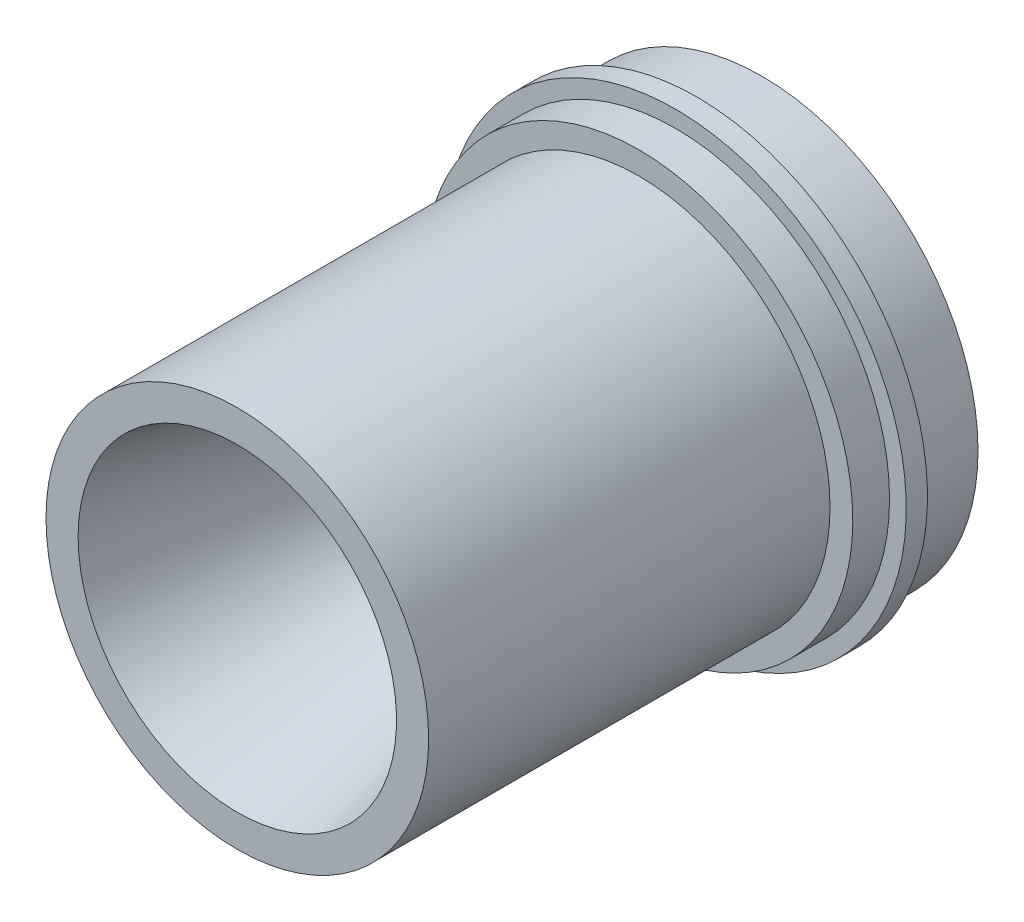
SolidWorks part; units mm, degrees
ref_plane "Front Plane" through (0, 0, 0) normal (0, 0, 1) x (1, 0, 0)
ref_plane "Top Plane" through (0, 0, 0) normal (0, 1, 0) x (1, 0, 0)
ref_plane "Right Plane" through (0, 0, 0) normal (1, 0, 0) x (0, 0, -1)
sketch "Sketch1" plane through (0, 0, 0) normal (0, 1, 0) x (1, 0, 0)
  line L0 (34.5, 0) -> (32.33, 0)
  line L1 (34.5, 0) -> (34.5, -3.1704)
  line L2 (34.5, -3.1704) -> (32, -3.1704)
  line L3 (32, -3.1704) -> (32, -8.6704)
  line L4 (32, -8.6704) -> (28.6, -8.6704)
  line L5 (28.6, -8.6704) -> (28.6, -68.6704)
  line L6 (28.6, -68.6704) -> (23.8, -68.6704)
  line L7 (0, 0) -> (0, -54.7049)
  line L8 (32.33, 0) -> (32.33, 9.72)
  line L9 (32.33, 9.72) -> (26.83, 9.72)
  line L13 (9.779, -13.6226) -> (23.8, -68.6704)
  line L16 (9.779, -8.8474) -> (9.779, -13.6226)
  spline S0 degree 1 poles (9.779, -8.8474) (9.779, 0) knots 0 0 1 1
  spline S1 degree 2 poles (9.779, 0) (14.4167, 10.528) (26.83, 9.72) knots 0 0 0 1 1 1
revolve "Revolve4" add sketch "Sketch1" angle 360 about L7
